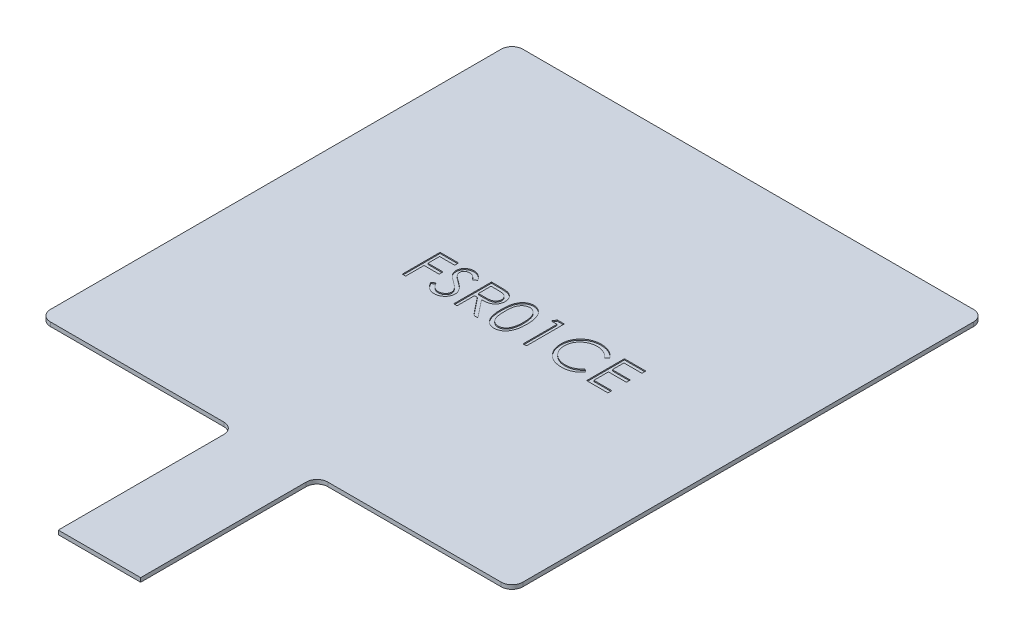
SolidWorks part; units mm, degrees
ref_plane "Front Plane" through (0, 0, 0) normal (0, 0, 1) x (1, 0, 0)
ref_plane "Top Plane" through (0, 0, 0) normal (0, 1, 0) x (1, 0, 0)
ref_plane "Right Plane" through (0, 0, 0) normal (1, 0, 0) x (0, 0, -1)
sketch "Sketch1" plane through (0, 0, 0) normal (0, 1, 0) x (1, 0, 0)
  line L1 (-19.85, -19.85) -> (19.85, -19.85)
  line L2 (-19.85, -19.85) -> (-19.85, 19.85)
  line L3 (-19.85, 19.85) -> (19.85, 19.85)
  line L4 (19.85, -19.85) -> (19.85, 19.85)
  line L5 (-19.85, -19.85) -> (19.85, 19.85) construction
  line L6 (-19.85, 19.85) -> (19.85, -19.85) construction
  line L7 (-21.845, -21.845) -> (21.845, -21.845)
  line L8 (-21.845, -21.845) -> (-21.845, 21.845)
  line L9 (-21.845, 21.845) -> (21.845, 21.845)
  line L10 (21.845, -21.845) -> (21.845, 21.845)
  line L11 (-21.845, -21.845) -> (21.845, 21.845) construction
  line L12 (-21.845, 21.845) -> (21.845, -21.845) construction
  line L13 (-3.81, -21.845) -> (3.81, -21.845)
  line L14 (-3.81, -21.845) -> (-3.81, -38.155)
  line L15 (-3.81, -38.155) -> (3.81, -38.155)
  line L16 (3.81, -21.845) -> (3.81, -38.155)
  point P0 (0, 0)
  point P6 (0, 0)
  point P15 (0, 0)
  point P16 (0, -38.155)
  dimension "D1" = 43.69
  dimension "D2" = 43.69
  dimension "D3" = 39.7
  dimension "D4" = 39.7
  dimension "D5" = 7.62
  dimension "D6" = 60
extrude "Boss-Extrude1" add sketch "Sketch1" along normal blind 0.375 contours L16 L7 L14 L15 | L1 L4 L3 L2 | L7 L10 L9 L8 L4 L1 L2 L3
sketch "Sketch2" plane through (0, 0.375, 0) normal (0, 1, 0) x (1, 0, 0)
  text T0 "FSR01CE"
  point P1 (0, 0)
  dimension "D1" = 8.85
  dimension "D2" = 1.75
extrude "Cut-Extrude1" cut sketch "Sketch2" against normal blind 0.1
fillet "Fillet1" radius 1 6 edges at (-21.845, 0.1875, 21.845) (-3.81, 0.1875, 21.845) (3.81, 0.1875, 21.845) (21.845, 0.1875, 21.845) (21.845, 0.1875, -21.845) (-21.845, 0.1875, -21.845)
